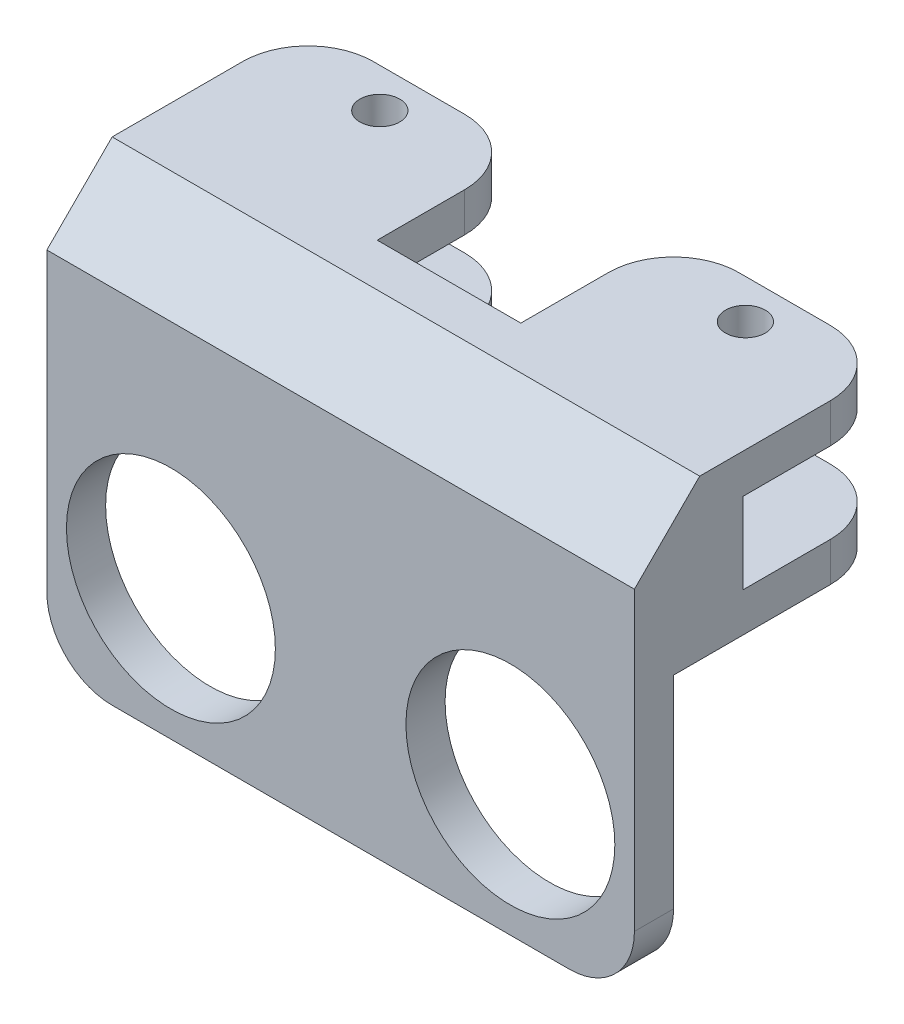
SolidWorks part; units mm, degrees
ref_plane "Front Plane" through (0, 0, 0) normal (0, 0, 1) x (1, 0, 0)
ref_plane "Top Plane" through (0, 0, 0) normal (0, 1, 0) x (1, 0, 0)
ref_plane "Right Plane" through (0, 0, 0) normal (1, 0, 0) x (0, 0, -1)
sketch "Sketch1" plane through (0, 0, 0) normal (0, 0, 1) x (1, 0, 0)
  line L0 (-17.5, -10.5) -> (17.5, -10.5)
  line L1 (22.5, -5.5) -> (22.5, 10.5)
  line L3 (-22.5, 10.5) -> (-22.5, -5.5)
  line L6 (-22.5, 10.5) -> (-22.5, 13)
  line L7 (-22.5, 13) -> (22.5, 13)
  line L8 (22.5, 10.5) -> (22.5, 13)
  circle A0 centre (13, -0.5) radius 8
  circle A1 centre (-13, -0.5) radius 8
  arc A2 (17.5, -10.5) -> (22.5, -5.5) centre (17.5, -5.5) ccw
  arc A3 (-22.5, -5.5) -> (-17.5, -10.5) centre (-17.5, -5.5) ccw
  dimension "D1" = 35
extrude "Boss-Extrude1" add sketch "Sketch1" along normal blind 3
sketch "Sketch2" plane through (0, 0, 0) normal (0, 0, -1) x (-1, 0, 0)
  line L0 (22.5, 13) -> (22.5, -5.5) construction
  line L1 (-22.5, 13) -> (22.5, 13)
  line L2 (-22.5, 13) -> (-22.5, 10)
  line L3 (-22.5, 10) -> (22.5, 10)
  line L4 (22.5, 13) -> (22.5, 10)
  line L6 (-5.5, 13) -> (5.5, 13)
  line L7 (-5.5, 13) -> (-5.5, 10)
  line L8 (-5.5, 10) -> (5.5, 10)
  line L9 (5.5, 13) -> (5.5, 10)
  point P11 (0, 10)
  point P12 (0, 10)
  line M6 (22.5, -5.5) -> (22.5, 13)
  line M7 (22.5, 13) -> (-22.5, 13)
  line M8 (-22.5, 13) -> (-22.5, -5.5)
  dimension "D1" = 3
  dimension "D2" = 11
extrude "Boss-Extrude2" add sketch "Sketch2" along normal blind 17 contours L7 L3 M7 M8 | L9 L3 M7 M6
sketch "Sketch3" plane through (0, 13, 0) normal (0, 1, 0) x (1, 0, 0)
  line L0 (22.5, -3) -> (22.5, 17) construction
  line L1 (-22.5, -3) -> (22.5, -3)
  line L2 (-22.5, -3) -> (-22.5, 0)
  line L3 (-22.5, 0) -> (22.5, 0)
  line L4 (22.5, -3) -> (22.5, 0)
extrude "Boss-Extrude3" add sketch "Sketch3" along normal blind 9.2
sketch "Sketch4" plane through (-5.5, 0, 0) normal (1, 0, 0) x (0, 0, -1)
  line L0 (17, 10) -> (0, 10) construction
  line L1 (0, 13) -> (5.3, 13)
  line L2 (0, 13) -> (0, 10)
  line L3 (0, 10) -> (5.3, 10)
  line L4 (5.3, 13) -> (5.3, 10)
  dimension "D1" = 5.3
extrude "Boss-Extrude4" add sketch "Sketch4" along normal up to next
sketch "Sketch6" plane through (0, 13, 0) normal (0, 1, 0) x (1, 0, 0)
  line L0 (22.5, 0) -> (22.5, 17) construction
  line L1 (-22.5, 0) -> (22.5, 0)
  line L2 (-22.5, 0) -> (-22.5, 5.3)
  line L3 (-22.5, 5.3) -> (22.5, 5.3)
  line L4 (22.5, 0) -> (22.5, 5.3)
extrude "Boss-Extrude5" add sketch "Sketch6" along normal up to surface (9.2 mm away) contours L2 L1 L4 L3 up to face at (0, 22.2, 1.5)
sketch "Sketch7" plane through (0, 0, -5.3) normal (0, 0, -1) x (-1, 0, 0)
  line L0 (22.5, 22.2) -> (22.5, 13) construction
  line L1 (-22.5, 22.2) -> (-5.5, 22.2)
  line L2 (-22.5, 22.2) -> (-22.5, 19.2)
  line L3 (-22.5, 19.2) -> (-5.5, 19.2)
  line L4 (22.5, 22.2) -> (22.5, 19.2)
  line L5 (5.5, 22.2) -> (22.5, 22.2)
  line L7 (-5.5, 19.2) -> (-5.5, 22.2)
  line L9 (5.5, 19.2) -> (5.5, 22.2)
  line L10 (5.5, 19.2) -> (22.5, 19.2)
  dimension "D1" = 3
extrude "Boss-Extrude6" add sketch "Sketch7" along normal through all
sketch "Sketch8" plane through (0, 22.2, 0) normal (0, 1, 0) x (1, 0, 0)
  line L0 (5.5, 17) -> (22.5, 17) construction
  line L1 (5.5, 17) -> (5.5, 5.3) construction
  line L2 (0, -11) -> (0, 11) construction
  circle A0 centre (14, 14) radius 1.525
  circle A1 centre (-14, 14) radius 1.525
  dimension "D2" = 3.05
  dimension "D1" = 3
  dimension "D3" = 8.5
extrude "Cut-Extrude1" cut sketch "Sketch8" against normal through all
chamfer "Chamfer1" distance 5 angle 45 1 edges at (0, 22.2, 3)
fillet "Fillet1" radius 5 8 edges at (-5.5, 11.5, -17) (-22.5, 11.5, -17) (-22.5, 20.7, -17) (-5.5, 20.7, -17) (5.5, 11.5, -17) (5.5, 20.7, -17) (22.5, 20.7, -17) (22.5, 11.5, -17)
